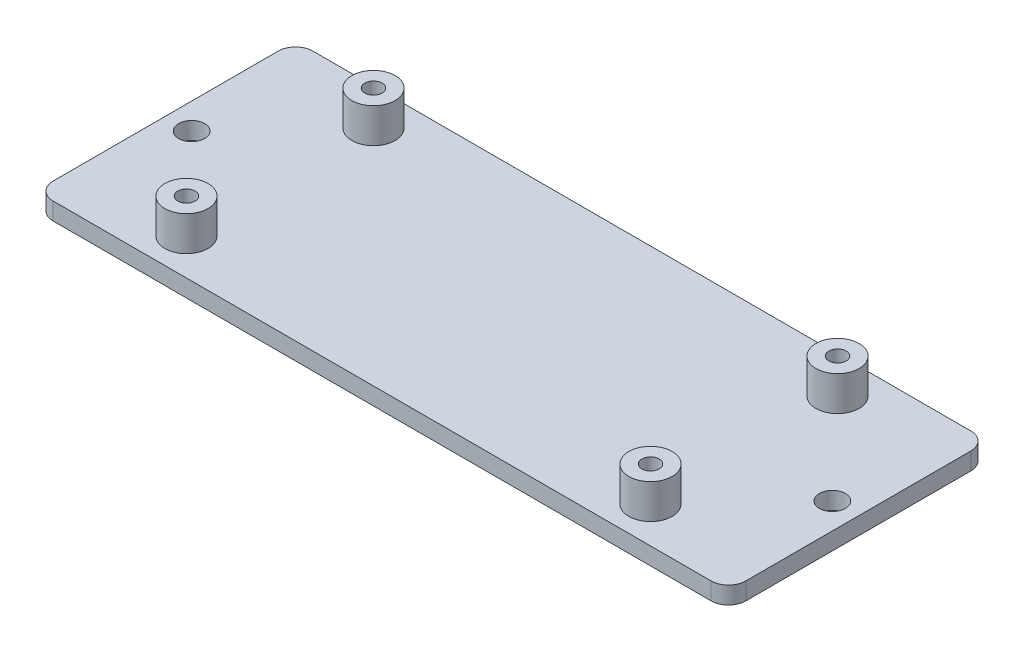
SolidWorks part; units mm, degrees
ref_plane "Front Plane" through (0, 0, 0) normal (0, 0, 1) x (1, 0, 0)
ref_plane "Top Plane" through (0, 0, 0) normal (0, 1, 0) x (1, 0, 0)
ref_plane "Right Plane" through (0, 0, 0) normal (1, 0, 0) x (0, 0, -1)
sketch "Base" plane through (0, 0, 0) normal (0, 1, 0) x (1, 0, 0)
  line L0 (50.8, -961.9) -> (50.8, 49038.1) construction
  line L1 (2.54, 0) -> (99.06, 0)
  line L2 (0, 2.54) -> (0, 35.56)
  line L3 (2.54, 38.1) -> (99.06, 38.1)
  line L4 (101.6, 2.54) -> (101.6, 35.56)
  line L5 (-1000, 19.05) -> (49000, 19.05) construction
  arc A0 (0, 35.56) -> (2.54, 38.1) centre (2.54, 35.56) cw
  arc A1 (101.6, 35.56) -> (99.06, 38.1) centre (99.06, 35.56) ccw
  arc A2 (99.06, 0) -> (101.6, 2.54) centre (99.06, 2.54) ccw
  arc A3 (2.54, 0) -> (0, 2.54) centre (2.54, 2.54) cw
  circle A4 centre (3.81, 19.05) radius 1.905
  circle A5 centre (97.79, 19.05) radius 1.905
  point P9 (101.6, 38.1)
  point P12 (101.6, 0)
  point P15 (0, 0)
  point P19 (50.8, 38.1)
  point P22 (0, 19.05)
  dimension "D3" = 2.54
  dimension "D4" = 2.54
  dimension "D5" = 3.81
  dimension "D1" = 101.6
  dimension "D2" = 38.1
extrude "Boss-ExtrudeBase" add sketch "Base" along normal blind 2.54
ref_plane "TopBase" through (0, 2.54, 0) normal (0, 1, 0) x (1, 0, 0)
sketch "Standoffs" plane through (0, 2.54, 0) normal (0, 1, 0) x (1, 0, 0)
  line L0 (50.8, -961.9) -> (50.8, 49038.1) construction
  line L1 (99.06, 38.1) -> (2.54, 38.1) construction
  line L2 (-898.4, 19.05) -> (49101.6, 19.05) construction
  line L3 (101.6, 2.54) -> (101.6, 35.56) construction
  line L4 (0, 35.56) -> (0, 2.54) construction
  circle A0 centre (16.764, 32.766) radius 3.175
  circle A1 centre (84.836, 32.766) radius 3.175
  circle A2 centre (84.836, 5.334) radius 3.175
  circle A3 centre (16.764, 5.334) radius 3.175
  circle A4 centre (16.764, 32.766) radius 1.27
  circle A5 centre (84.836, 32.766) radius 1.27
  circle A6 centre (84.836, 5.334) radius 1.27
  circle A7 centre (16.764, 5.334) radius 1.27
  point P5 (50.8, 38.1)
  point P10 (101.6, 19.05)
  point P12 (50.8, 19.05)
  dimension "D1" = 6.35
  dimension "D2" = 34.036
  dimension "D3" = 13.716
extrude "Boss-Extrude2" add sketch "Standoffs" along normal blind 5.08
